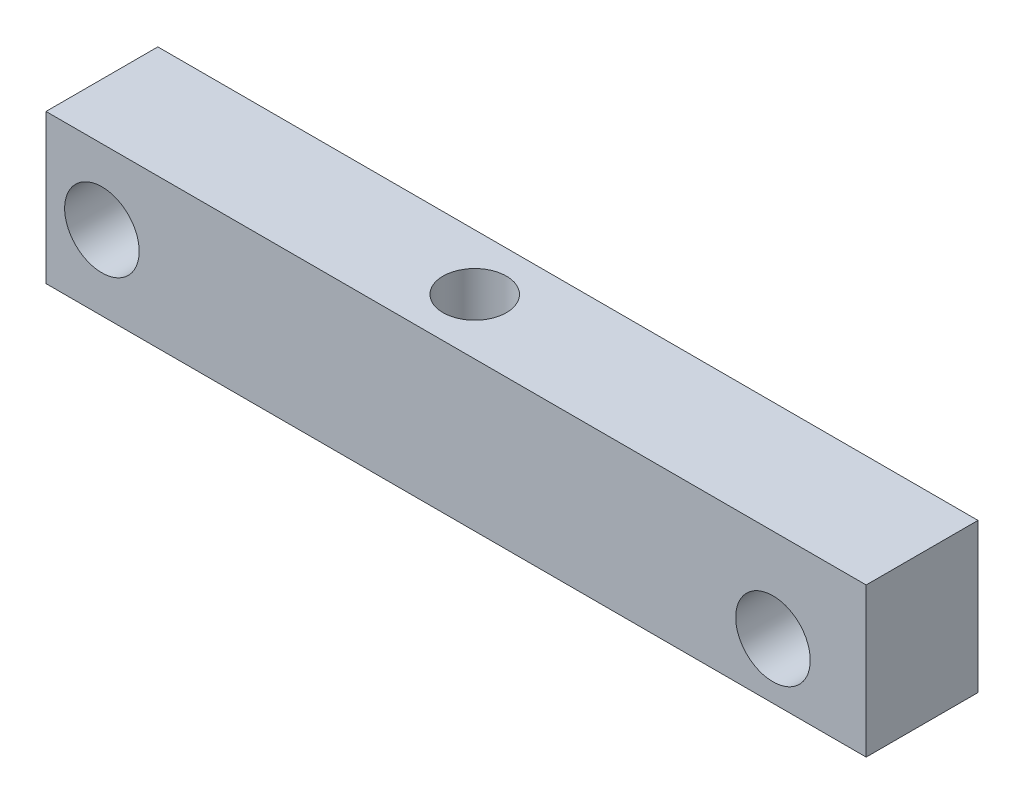
SolidWorks part; units mm, degrees
ref_plane "Alzado" through (0, 0, 0) normal (0, 0, 1) x (1, 0, 0)
ref_plane "Planta" through (0, 0, 0) normal (0, 1, 0) x (1, 0, 0)
ref_plane "Vista lateral" through (0, 0, 0) normal (1, 0, 0) x (0, 0, -1)
sketch "Croquis1" plane through (0, 0, 0) normal (0, 0, 1) x (1, 0, 0)
  line L1 (-11, -2) -> (11, -2)
  line L2 (-11, -2) -> (-11, 2)
  line L3 (-11, 2) -> (11, 2)
  line L4 (11, -2) -> (11, 2)
  line L5 (-11, -2) -> (11, 2) construction
  line L6 (-11, 2) -> (11, -2) construction
  point P0 (0, 0)
  dimension "D1" = 22
  dimension "D2" = 4
extrude "Saliente-Extruir1" add sketch "Croquis1" along normal blind 3
sketch "Croquis2" plane through (0, 2, 0) normal (0, 1, 0) x (1, 0, 0)
  line L0 (-11, -1.5) -> (11, -1.5) construction
  line L5 (-11, -3) -> (-11, 0) construction
  line L6 (11, -3) -> (11, 0) construction
  circle A0 centre (-1, -1.5) radius 0.85
  dimension "D1" = 1.7
  dimension "D2" = 12
extrude "Cortar-Extruir1" cut sketch "Croquis2" against normal blind 3
sketch "Croquis3" plane through (0, 0, 3) normal (0, 0, 1) x (1, 0, 0)
  line L0 (-11, 2) -> (-8, -2) construction
  line L1 (-11, -2) -> (11, -2) construction
  line L2 (-11, 2) -> (-11, -2) construction
  line L3 (6, 1) -> (11, -2) construction
  circle A0 centre (8.5, -0.5) radius 1
  circle A1 centre (-9.5, 0) radius 1
  dimension "D4" = 2
  dimension "D5" = 2
  dimension "D1" = 3
  dimension "D2" = 5
  dimension "D3" = 3
extrude "Cortar-Extruir2" cut sketch "Croquis3" against normal up to next
